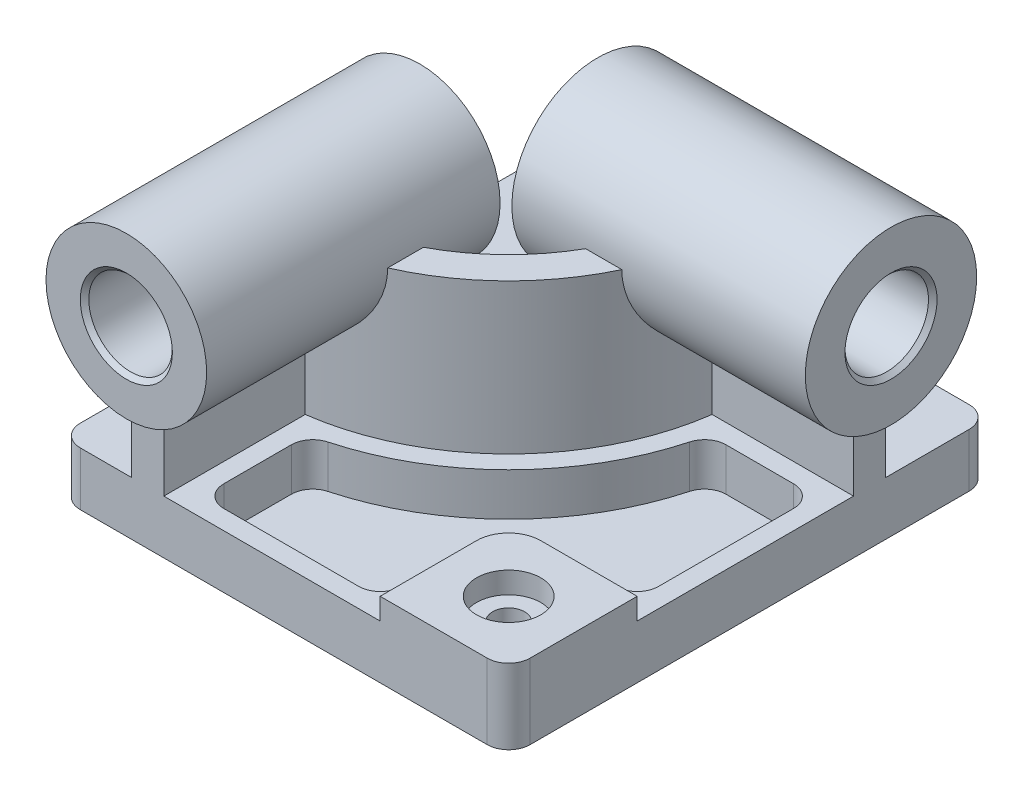
SolidWorks part; units mm, degrees
material "Alloy Steel"
ref_plane "Front Plane" through (0, 0, 0) normal (0, 0, 1) x (1, 0, 0)
ref_plane "Top Plane" through (0, 0, 0) normal (0, 1, 0) x (1, 0, 0)
ref_plane "Right Plane" through (0, 0, 0) normal (1, 0, 0) x (0, 0, -1)
sketch "Sketch1" plane through (0, 0, 0) normal (0, 1, 0) x (1, 0, 0)
  line L0 (0, 0) -> (0, -176) construction
  line L1 (-24, 49) -> (166, 49)
  line L2 (-34, 39) -> (-34, -166)
  line L3 (-24, -176) -> (166, -176)
  line L4 (176, 39) -> (176, -166)
  line L6 (21.1729, -100.3509) -> (22.0551, -100.3509) construction
  line L8 (0, 0) -> (176, 0) construction
  arc A0 (-24, 49) -> (-34, 39) centre (-24, 39) ccw
  arc A1 (-34, -166) -> (-24, -176) centre (-24, -166) ccw
  arc A2 (166, -176) -> (176, -166) centre (166, -166) ccw
  arc A3 (166, 49) -> (176, 39) centre (166, 39) cw
  dimension "D5" = 10
  dimension "D1" = 176
  dimension "D2" = 176
  dimension "D3" = 225
  dimension "D4" = 210
extrude "Boss-Extrude1" add sketch "Sketch1" along normal blind 25
sketch "Sketch2" plane through (0, 25, 0) normal (0, 1, 0) x (1, 0, 0)
  line L0 (0, -96) -> (0, -176)
  line L1 (-24, -176) -> (166, -176) construction
  line L2 (96, 0) -> (176, 0)
  line L3 (176, -166) -> (176, 39) construction
  line L4 (15, -109.9818) -> (15, -176)
  line L5 (109.9818, -15) -> (176, -15)
  line L6 (176, 0) -> (176, -15)
  line L7 (0, -176) -> (15, -176)
  arc A0 (0, -96) -> (96, 0) centre (0, 0) ccw
  arc A1 (15, -109.9818) -> (109.9818, -15) centre (0, 0) ccw
  dimension "D1" = 80
  dimension "D2" = 15
extrude "Boss-Extrude2" add sketch "Sketch2" along normal blind 95 from surface at -25 starting at face at (71, 0, 63.5)
sketch "Sketch3" plane through (0, 25, 0) normal (0, 1, 0) x (1, 0, 0)
  line L0 (15, -176) -> (166, -176) construction
  line L1 (131, -116) -> (176, -116)
  line L2 (116, -131) -> (116, -176)
  line L3 (116, -176) -> (166, -176)
  line L4 (176, -116) -> (176, -166)
  line L5 (176, -166) -> (176, -15) construction
  arc A0 (166, -176) -> (176, -166) centre (166, -166) ccw construction
  arc A1 (166, -176) -> (176, -166) centre (166, -166) ccw
  arc A2 (131, -116) -> (116, -131) centre (131, -131) ccw
  dimension "D3" = 15
  dimension "D1" = 60
  dimension "D2" = 60
extrude "Boss-Extrude3" add sketch "Sketch3" along normal blind 10
hole_wizard "CBORE for M8 Hex Head Bolt1" positions "Sketch5" profile "Sketch4" counterbore size "M8" standard "ANSI Metric" end condition through all
sketch "Sketch5" plane through (0, 35, 0) normal (0, 1, 0) x (1, 0, 0)
  line L0 (116, -176) -> (166, -176) construction
  line L2 (176, -166) -> (176, -116) construction
  point P0 (146, -146)
  dimension "D1" = 30
  dimension "D2" = 30
sketch "Sketch4" plane through (146, 35, 146) normal (1, 0, 0) x (0, 0, 1)
  line L0 (0, 0) -> (0, 35)
  line L1 (0, 35) -> (7.5, 35)
  line L3 (7.5, 35) -> (7.5, 10)
  line L4 (7.5, 10) -> (15, 10)
  line L5 (15, 10) -> (15, 0)
  line L7 (15, 0) -> (0, 0)
  line L11 (0, -6.35) -> (0, 107.95) construction
  dimension "Thru Hole Dia." = 15
  dimension "Thru Hole Depth" = 35
  dimension "C'Bore Dia." = 30
  dimension "C'Bore Depth" = 10
sketch "Sketch6" plane through (0, 25, 0) normal (0, 1, 0) x (1, 0, 0)
  line L6 (107, -167) -> (107, -131)
  line L7 (107, -157) -> (107, -131)
  line L8 (131, -107) -> (167, -107)
  line L9 (131, -107) -> (157, -107)
  line L10 (167, -24) -> (117.5755, -24)
  line L11 (157, -24) -> (125.4751, -24)
  line L12 (24, -167) -> (107, -167)
  line L13 (24, -117.5755) -> (24, -167)
  line L14 (24, -125.4751) -> (24, -157)
  line L15 (167, -107) -> (167, -24)
  line L18 (34, -167) -> (97, -167)
  line L21 (167, -97) -> (167, -34)
  arc A0 (167, -97) -> (157, -107) centre (157, -97) cw
  arc A1 (107, -157) -> (97, -167) centre (97, -157) cw
  arc A2 (24, -125.4751) -> (31.3846, -115.8232) centre (34, -125.4751) cw
  arc A3 (115.8232, -31.3846) -> (125.4751, -24) centre (125.4751, -34) cw
  arc A4 (131, -107) -> (107, -131) centre (131, -131) ccw
  arc A5 (24, -117.5755) -> (117.5755, -24) centre (0, 0) ccw
  arc A6 (131, -107) -> (107, -131) centre (131, -131) ccw
  arc A7 (31.3846, -115.8232) -> (115.8232, -31.3846) centre (0, 0) ccw
  arc A8 (167, -34) -> (157, -24) centre (157, -34) ccw
  arc A9 (34, -167) -> (24, -157) centre (34, -157) cw
  dimension "D2" = 10
  dimension "D3" = 10
  dimension "D1" = 9
extrude "Cut-Extrude1" cut sketch "Sketch6" against normal offset from surface (20 mm away) 5 up to face at (146, 0, 153.5)
sketch "Sketch7" plane through (0, 0, 176) normal (0, 0, 1) x (1, 0, 0)
  line L0 (0, 95) -> (15, 95) construction
  circle A0 centre (7.5, 95) radius 37.5
  dimension "D1" = 75
extrude "Boss-Extrude4" add sketch "Sketch7" against normal blind 137 from offset 10
sketch "Sketch8" plane through (176, 0, 0) normal (1, 0, 0) x (0, 0, -1)
  line L0 (-15, 95) -> (0, 95) construction
  circle A0 centre (-7.5, 95) radius 40
  dimension "D1" = 80
extrude "Boss-Extrude5" add sketch "Sketch8" against normal blind 137 from offset 10
sketch "Sketch9" plane through (0, 0, 186) normal (0, 0, 1) x (1, 0, 0)
  circle A0 centre (7.5, 95) radius 19.5
  dimension "D1" = 39
extrude "Cut-Extrude2" cut sketch "Sketch9" against normal up to next
sketch "Sketch10" plane through (186, 0, 0) normal (1, 0, 0) x (0, 0, -1)
  circle A0 centre (-7.5, 95) radius 19.5
  dimension "D1" = 39
extrude "Cut-Extrude3" cut sketch "Sketch10" against normal up to next
chamfer "Chamfer1" distance 2 angle 45 4 edges at (49, 95, -12) (27, 95, 49) (186, 95, -12) (27, 95, 186)
equation "\"A\" = 225"
equation "\"D1@Sketch1\"=\"C\""
equation "\"D2@Sketch1\"=\"C\""
equation "\"B\" = 210"
equation "\"D3@Sketch1\"=\"A\""
equation "\"C\" = 176"
equation "\"D4@Sketch1\"=\"B\""
equation "\"D1@Sketch7\"=\"X\""
equation "\"D\" = 137"
equation "\"D1@Boss-Extrude4\"=\"D\""
equation "\"D1@Sketch8\"=\"Y\""
equation "\"D1@Boss-Extrude5\"=\"D\""
equation "\"E\"= 39"
equation "\"D1@Sketch9\"=\"E\""
equation "\"D1@Sketch10\"=\"E\""
equation "\"X\"= \"A\" / 3"
equation "\"Y\"= \"B\" / 3 + 10"
